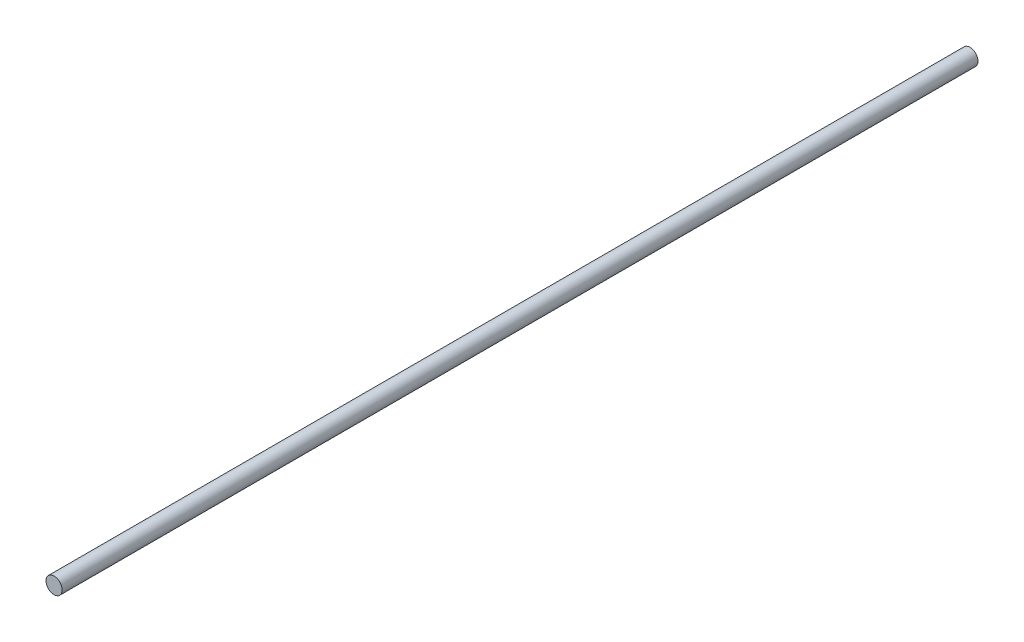
SolidWorks part; units mm, degrees
ref_plane "Plan de face" through (0, 0, 0) normal (0, 0, 1) x (1, 0, 0)
ref_plane "Plan de dessus" through (0, 0, 0) normal (0, 1, 0) x (1, 0, 0)
ref_plane "Plan de droite" through (0, 0, 0) normal (1, 0, 0) x (0, 0, -1)
sketch "Esquisse1" plane through (0, 0, 0) normal (0, 0, 1) x (1, 0, 0)
  circle A0 centre (0, 0) radius 7.5
  dimension "D1" = 15
extrude "Boss.-Extru.1" add sketch "Esquisse1" along normal blind 850
